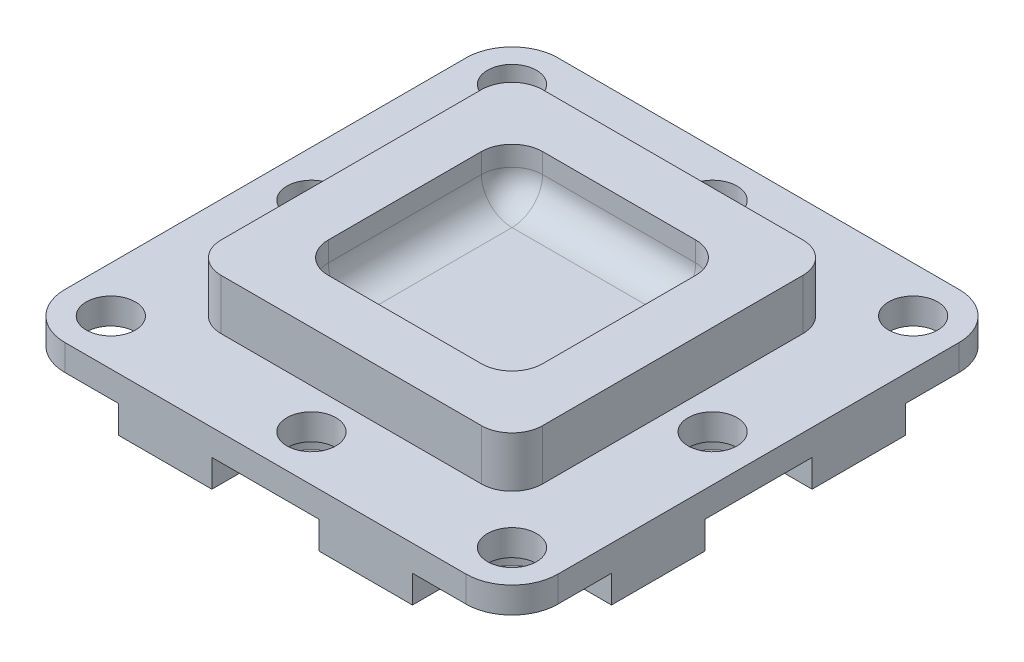
SolidWorks part; units mm, degrees
material "6061-T6 (SS)"
ref_plane "Front Plane" through (0, 0, 0) normal (0, 0, 1) x (1, 0, 0)
ref_plane "Top Plane" through (0, 0, 0) normal (0, 1, 0) x (1, 0, 0)
ref_plane "Right Plane" through (0, 0, 0) normal (1, 0, 0) x (0, 0, -1)
sketch "Sketch1" plane through (0, 0, 0) normal (0, 1, 0) x (1, 0, 0)
  line L5 (-16.1, -16.1) -> (16.1, -16.1)
  line L6 (-16.1, -16.1) -> (-16.1, 16.1)
  line L7 (-16.1, 16.1) -> (16.1, 16.1)
  line L8 (16.1, -16.1) -> (16.1, 16.1)
  line L9 (-16.1, -16.1) -> (16.1, 16.1) construction
  line L10 (-16.1, 16.1) -> (16.1, -16.1) construction
  point P0 (0, 0)
  dimension "D1" = 32.2
extrude "Boss-Extrude1" add sketch "Sketch1" along normal blind 3.5
sketch "Sketch2" plane through (0, 3.5, 0) normal (0, 1, 0) x (1, 0, 0)
  line L5 (-10.5, 10.5) -> (10.5, 10.5)
  line L6 (-10.5, 10.5) -> (-10.5, -10.5)
  line L7 (-10.5, -10.5) -> (10.5, -10.5)
  line L8 (10.5, 10.5) -> (10.5, -10.5)
  line L9 (-10.5, 10.5) -> (10.5, -10.5) construction
  line L10 (-10.5, -10.5) -> (10.5, 10.5) construction
  point P0 (0, 0)
  dimension "D1" = 21
extrude "Boss-Extrude3" add sketch "Sketch2" along normal blind 3.3
fillet "Fillet1" radius 3 4 edges at (-16.1, 1.75, 16.1) (16.1, 1.75, 16.1) (16.1, 1.75, -16.1) (-16.1, 1.75, -16.1)
fillet "Fillet2" radius 2 4 edges at (-10.5, 5.15, -10.5) (10.5, 5.15, -10.5) (10.5, 5.15, 10.5) (-10.5, 5.15, 10.5)
sketch "Sketch10" plane through (0, 6.8, 0) normal (0, 1, 0) x (1, 0, 0)
  line L5 (-7, 7) -> (7, 7)
  line L6 (-7, 7) -> (-7, -7)
  line L7 (-7, -7) -> (7, -7)
  line L8 (7, 7) -> (7, -7)
  line L9 (-7, 7) -> (7, -7) construction
  line L10 (-7, -7) -> (7, 7) construction
  point P0 (0, 0)
  dimension "D1" = 14
extrude "Cut-Extrude2" cut sketch "Sketch10" against normal up to surface (3.3 mm away) up to face at (0, 3.5, 0)
fillet "Fillet3" radius 2 8 edges at (0, 3.5, 7) (7, 3.5, 0) (0, 3.5, -7) (-7, 3.5, 0) (-7, 5.15, 7) (7, 5.15, 7) (7, 5.15, -7) (-7, 5.15, -7)
sketch "Sketch9" plane through (0, 3.5, 0) normal (0, 1, 0) x (1, 0, 0)
  line L0 (13.1, 16.1) -> (-13.1, 16.1) construction
  circle A8 centre (0, 13.1) radius 1.6
  circle A22 centre (13.1, 0) radius 1.6
  circle A23 centre (0, -13.1) radius 1.6
  circle A24 centre (-13.1, 0) radius 1.6
  point P13 (0, 0)
  dimension "D1" = 3.2
  dimension "D2" = 3
extrude "Cut-Extrude1" cut sketch "Sketch9" against normal blind 7
sketch "Sketch11" plane through (0, 0, 0) normal (0, -1, 0) x (1, 0, 0)
  line L0 (-16.1, -13.1) -> (-16.1, 13.1) construction
  line L1 (-13.1, 16.1) -> (13.1, 16.1) construction
  circle A0 centre (-13.1, 13.1) radius 1.6
  circle A1 centre (13.1, 13.1) radius 1.6
  circle A2 centre (13.1, -13.1) radius 1.6
  circle A3 centre (-13.1, -13.1) radius 1.6
  point P15 (0, 0)
  dimension "D1" = 3.2
  dimension "D2" = 3
  dimension "D3" = 3
extrude "Cut-Extrude3" cut sketch "Sketch11" against normal through all
sketch "Sketch12" plane through (0, 0, 0) normal (0, -1, 0) x (1, 0, 0)
  line L0 (-13.1, 9.6) -> (-16.1, 9.6)
  line L1 (-16.1, -13.1) -> (-16.1, 13.1) construction
  line L2 (-16.1, 9.6) -> (-16.1, 16.1)
  line L3 (-16.1, 16.1) -> (-9.6, 16.1)
  line L4 (-9.6, 16.1) -> (-9.6, 13.1)
  line L5 (-13.1, 16.1) -> (13.1, 16.1) construction
  line L6 (-3.5, 13.1) -> (-3.5, 16.1)
  line L7 (-3.5, 16.1) -> (3.5, 16.1)
  line L8 (3.5, 16.1) -> (3.5, 13.1)
  line L21 (13.1, 3.5) -> (16.1, 3.5)
  line L22 (16.1, 3.5) -> (16.1, -3.5)
  line L23 (16.1, -3.5) -> (13.1, -3.5)
  line L24 (3.5, -13.1) -> (3.5, -16.1)
  line L25 (3.5, -16.1) -> (-3.5, -16.1)
  line L26 (-3.5, -16.1) -> (-3.5, -13.1)
  line L27 (-13.1, -3.5) -> (-16.1, -3.5)
  line L28 (-16.1, -3.5) -> (-16.1, 3.5)
  line L29 (-16.1, 3.5) -> (-13.1, 3.5)
  line L31 (9.6, 13.1) -> (9.6, 16.1)
  line L32 (9.6, 16.1) -> (16.1, 16.1)
  line L33 (16.1, 16.1) -> (16.1, 9.6)
  line L34 (16.1, 9.6) -> (13.1, 9.6)
  line L35 (13.1, -9.6) -> (16.1, -9.6)
  line L36 (16.1, -9.6) -> (16.1, -16.1)
  line L37 (16.1, -16.1) -> (9.6, -16.1)
  line L38 (9.6, -16.1) -> (9.6, -13.1)
  line L39 (-9.6, -13.1) -> (-9.6, -16.1)
  line L40 (-9.6, -16.1) -> (-16.1, -16.1)
  line L41 (-16.1, -16.1) -> (-16.1, -9.6)
  line L42 (-16.1, -9.6) -> (-13.1, -9.6)
  arc A0 (-13.1, 9.6) -> (-9.6, 13.1) centre (-13.1, 13.1) ccw
  arc A4 (-3.5, 13.1) -> (3.5, 13.1) centre (0, 13.1) ccw
  arc A11 (13.1, 3.5) -> (13.1, -3.5) centre (13.1, 0) ccw
  arc A12 (3.5, -13.1) -> (-3.5, -13.1) centre (0, -13.1) ccw
  arc A13 (-13.1, -3.5) -> (-13.1, 3.5) centre (-13.1, 0) ccw
  arc A14 (9.6, 13.1) -> (13.1, 9.6) centre (13.1, 13.1) ccw
  arc A15 (13.1, -9.6) -> (9.6, -13.1) centre (13.1, -13.1) ccw
  arc A16 (-9.6, -13.1) -> (-13.1, -9.6) centre (-13.1, -13.1) ccw
  point P40 (0, 0)
  point P57 (0, 0)
  dimension "D1" = 7
  dimension "D2" = 7
  dimension "D4" = 4
extrude "Cut-Extrude5" cut sketch "Sketch12" against normal blind 1.8
sketch "Sketch13" plane through (0, 0, 0) normal (0, -1, 0) x (-1, 0, 0)
  text T0 "<b>QCD Box</b>" font "Arial Narrow" height 2
extrude "Cut-Extrude6" cut sketch "Sketch13" against normal blind 0.5
equation "\"chip_size\"= 10mm"
equation "\"hold_edge\"= 1mm"
equation "\"holder_size\"= 32.2"
equation "\"M2P5\"=2.5"
equation "\"height_SMA\"= 7"
equation "\"tube_SMA\"= 4mm"
equation "\"separation_SMA\"= 10"
equation "\"D1@Cut-Extrude1\"=\"height_SMA\""
equation "\"D1@Sketch1\"=\"holder_size\""
equation "\"cavity_size\"=21"
equation "\"D1@Sketch2\"=\"cavity_size\""
